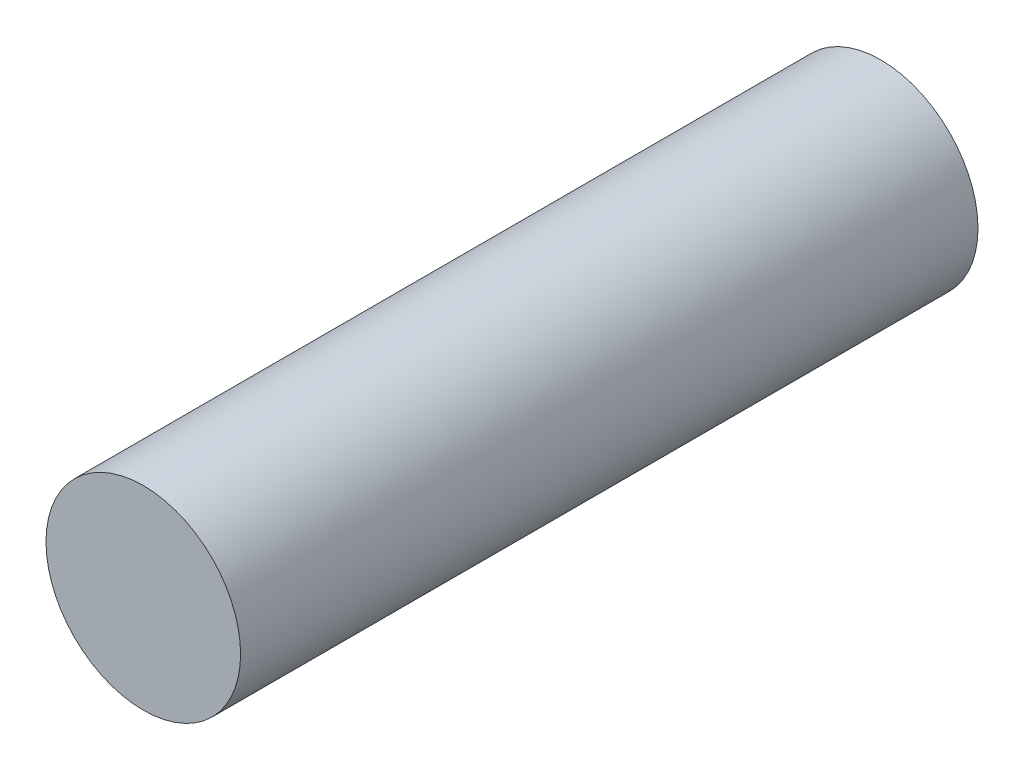
SolidWorks part; units mm, degrees
ref_plane "Front Plane" through (0, 0, 0) normal (0, 0, 1) x (1, 0, 0)
ref_plane "Top Plane" through (0, 0, 0) normal (0, 1, 0) x (1, 0, 0)
ref_plane "Right Plane" through (0, 0, 0) normal (1, 0, 0) x (0, 0, -1)
sketch "Sketch1" plane through (0, 0, 0) normal (0, 0, 1) x (1, 0, 0)
  circle A0 centre (0, 0) radius 30.1625
  dimension "D1" = 60.325
extrude "Boss-Extrude1" add sketch "Sketch1" along normal blind 228.6
